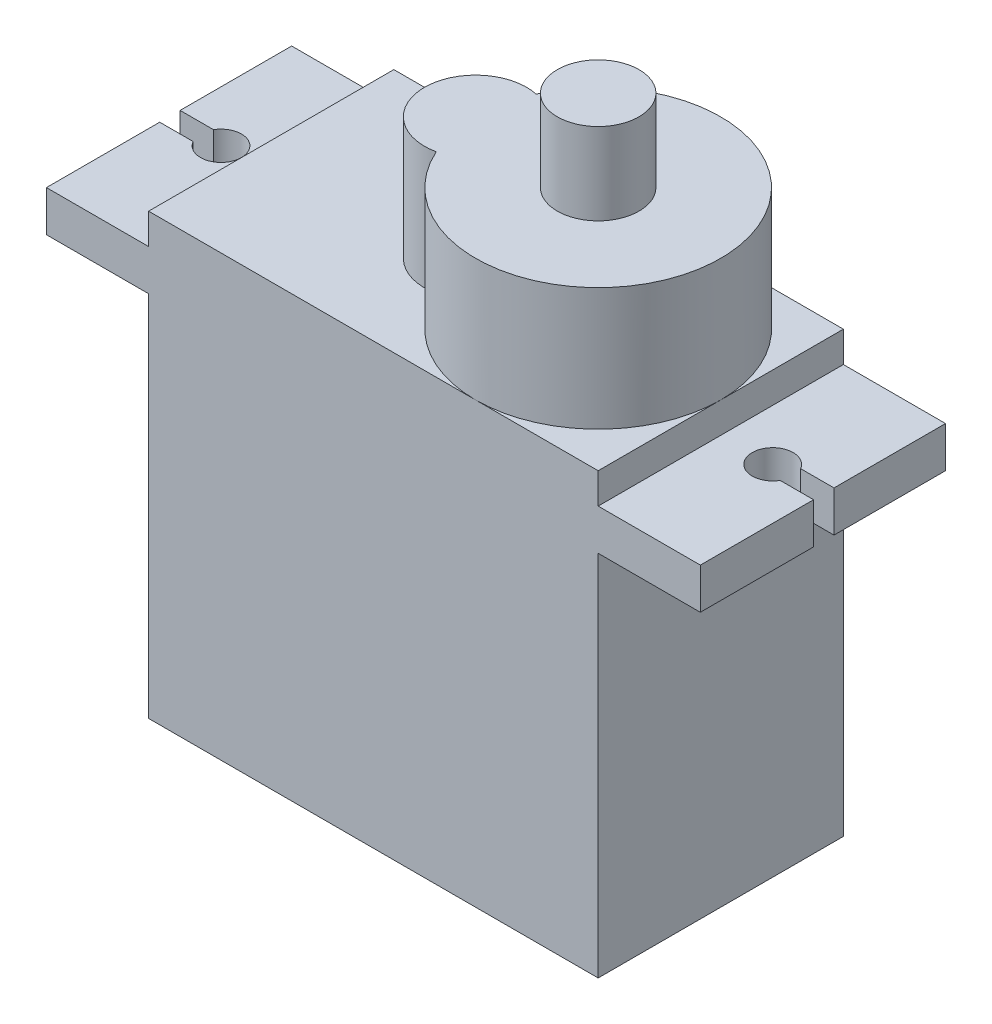
SolidWorks part; units mm, degrees
ref_plane "前视基准面" through (0, 0, 0) normal (0, 0, 1) x (1, 0, 0)
ref_plane "上视基准面" through (0, 0, 0) normal (0, 1, 0) x (1, 0, 0)
ref_plane "右视基准面" through (0, 0, 0) normal (1, 0, 0) x (0, 0, -1)
sketch "草图1" plane through (0, 0, 0) normal (0, 0, 1) x (1, 0, 0)
  line L0 (-11, 12.5368) -> (-16, 12.5368)
  line L1 (11, -5.4632) -> (-11, -5.4632)
  line L2 (11, -5.4632) -> (11, 12.5368)
  line L4 (-11, -5.4632) -> (-11, 12.5368)
  line L5 (-11, 14.5368) -> (-16, 14.5368)
  line L6 (11, 16.0368) -> (-11, 16.0368)
  line L7 (16, 14.5368) -> (11, 14.5368)
  line L8 (16, 14.5368) -> (16, 12.5368)
  line L9 (16, 12.5368) -> (11, 12.5368)
  line L10 (-16, 14.5368) -> (-16, 12.5368)
  line L11 (11, 16.0368) -> (11, 14.5368)
  line L13 (-11, 16.0368) -> (-11, 14.5368)
  point P0 (0, 0)
  point P6 (0, 10)
  point P11 (0, 15.2868)
  dimension "D1" = 22
  dimension "D2" = 18
  dimension "D3" = 32
  dimension "D4" = 5
  dimension "D5" = 2
  dimension "D7" = 1.5
extrude "凸台-拉伸1" add sketch "草图1" along normal blind 12
ref_plane "基准面4" through (0, 16.0368, 0) normal (0, 1, 0) x (1, 0, 0)
sketch "草图2" plane through (0, 16.0368, 0) normal (0, 1, 0) x (1, 0, 0)
  line L0 (11, 0) -> (-11, 0) construction
  line L1 (11, -12) -> (11, 0) construction
  arc A0 (-0.4792, -8.4451) -> (-0.4792, -3.5549) centre (5, -6) ccw
  arc A1 (-0.4792, -3.5549) -> (-0.4792, -8.4451) centre (-1, -6) ccw
  dimension "D1" = 12
  dimension "D4" = 5
  dimension "D2" = 6
  dimension "D3" = 6
extrude "凸台-拉伸3" add sketch "草图2" along normal blind 6
ref_plane "基准面6" through (0, 22.0368, 0) normal (0, 1, 0) x (1, 0, 0)
sketch "草图4" plane through (0, 22.0368, 0) normal (0, 1, 0) x (1, 0, 0)
  circle A1 centre (5, -6) radius 2
  arc A2 (-0.4792, -8.4451) -> (-0.4792, -3.5549) centre (5, -6) ccw construction
  dimension "D1" = 0
  dimension "D2" = 4
extrude "凸台-拉伸4" add sketch "草图4" along normal blind 4
ref_plane "基准面7" through (0, 14.5368, 0) normal (0, -1, 0) x (-1, 0, 0)
sketch "草图5" plane through (0, 14.5368, 0) normal (0, -1, 0) x (-1, 0, 0)
  line L0 (-16, -12) -> (-16, 0) construction
  line L1 (0, -1000) -> (0, 49000) construction
  line L2 (-14.366, -6.4583) -> (-16, -6.4583)
  line L4 (-14.366, -5.4583) -> (-16, -5.4583)
  line L5 (-16, -6.4583) -> (-16, -5.4583)
  line L6 (16, -6.4583) -> (16, -5.4583)
  line L7 (14.366, -5.4583) -> (16, -5.4583)
  line L8 (14.366, -6.4583) -> (16, -6.4583)
  arc A0 (-14.366, -6.4583) -> (-14.366, -5.4583) centre (-13.5, -5.9583) ccw
  arc A1 (14.366, -6.4583) -> (14.366, -5.4583) centre (13.5, -5.9583) cw
  point P4 (-14.5, -5.9583)
  point P16 (14.5, -5.9583)
  dimension "D1" = 2.5
  dimension "D2" = 1
extrude "切除-拉伸2" cut sketch "草图5" along normal through all
